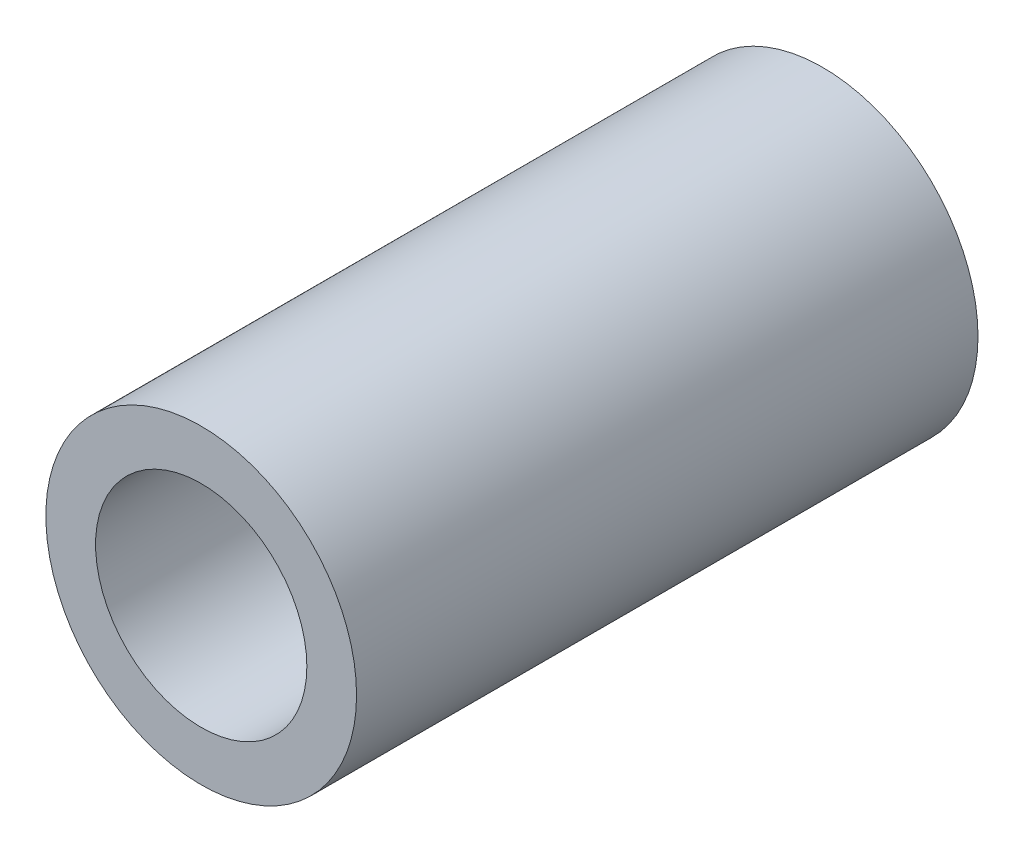
SolidWorks part; units mm, degrees
ref_plane "Front Plane" through (0, 0, 0) normal (0, 0, 1) x (1, 0, 0)
ref_plane "Top Plane" through (0, 0, 0) normal (0, 1, 0) x (1, 0, 0)
ref_plane "Right Plane" through (0, 0, 0) normal (1, 0, 0) x (0, 0, -1)
sketch "Sketch1" plane through (0, 0, 0) normal (0, 0, 1) x (1, 0, 0)
  circle A0 centre (0, 0) radius 2.5
  dimension "D1" = 5
extrude "Boss-Extrude1" add sketch "Sketch1" along normal blind 10
hole_wizard "M3 Clearance Hole1" positions "Sketch2" profile "Sketch3" hole size "M3" standard "ISO" end condition up to next
sketch "Sketch2" plane through (0, 0, 10) normal (0, 0, 1) x (1, 0, 0)
  point P0 (0, 0)
sketch "Sketch3" plane through (0, 0, 10) normal (1, 0, 0) x (0, -1, 0)
  line L0 (0, 0) -> (0, 10)
  line L1 (0, 10) -> (1.7, 10)
  line L2 (1.7, 10) -> (1.7, 0)
  line L5 (1.7, 0) -> (0, 0)
  line L11 (0, -6.35) -> (0, 107.95) construction
  dimension "Thru Hole Dia." = 3.4
  dimension "Thru Hole Depth" = 10
